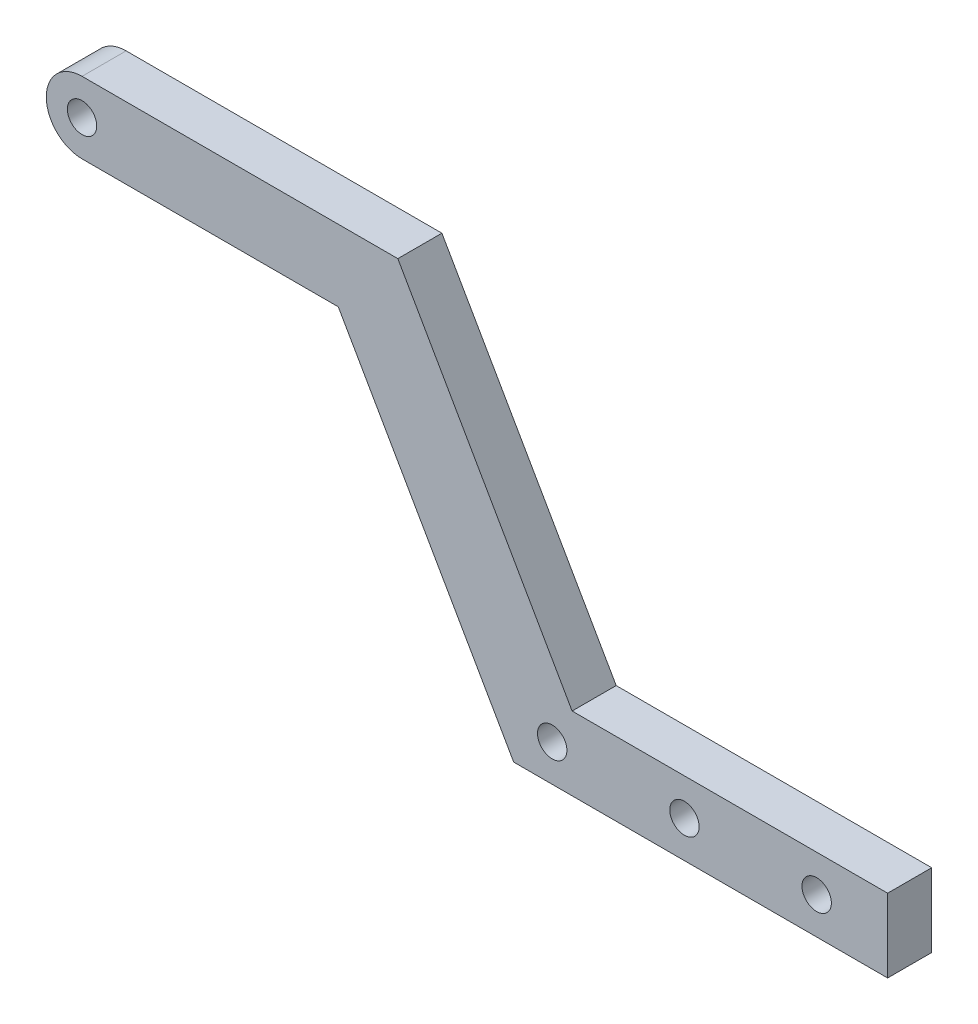
SolidWorks part; units mm, degrees
ref_plane "前视基准面" through (0, 0, 0) normal (0, 0, 1) x (1, 0, 0)
ref_plane "上视基准面" through (0, 0, 0) normal (0, 1, 0) x (1, 0, 0)
ref_plane "右视基准面" through (0, 0, 0) normal (1, 0, 0) x (0, 0, -1)
sketch "草图1" plane through (0, 0, 0) normal (0, 0, 1) x (1, 0, 0)
  line L0 (28.616, -12.9421) -> (28.616, -7.9421)
  line L1 (28.616, -7.9421) -> (7.1415, -7.9421)
  line L4 (28.616, -12.9421) -> (3.1652, -12.9421)
  line L7 (5.7862, -10.4421) -> (14.7862, -10.4421) construction
  line L8 (14.7862, -10.4421) -> (23.7862, -10.4421) construction
  line L9 (5.7862, -10.4421) -> (-26.2138, -10.4421) construction
  line L10 (-26.2138, -10.4421) -> (-26.2138, 10.3587) construction
  line L11 (-26.2138, 12.7925) -> (-4.7212, 12.7925)
  line L12 (-26.2138, 7.925) -> (-8.7732, 7.925)
  line L13 (-4.7212, 12.7925) -> (7.1415, -7.9421)
  line L14 (3.1652, -12.9421) -> (-8.7732, 7.925)
  line L15 (14.7862, -10.4421) -> (14.7862, -7.9421) construction
  line L16 (14.7862, -10.4421) -> (14.7862, -12.9421) construction
  circle A2 centre (5.7862, -10.4421) radius 1
  circle A3 centre (14.7862, -10.4421) radius 1
  circle A4 centre (23.7862, -10.4421) radius 1
  circle A5 centre (-26.2138, 10.3587) radius 1
  arc A6 (-26.2138, 7.925) -> (-26.2138, 12.7925) centre (-26.2138, 10.3587) cw
  dimension "D2" = 5
  dimension "D1" = 9
extrude "凸台-拉伸1" add sketch "草图1" along normal blind 3 contours L11 L13 L1 L0 L4 L14 L12 A6
